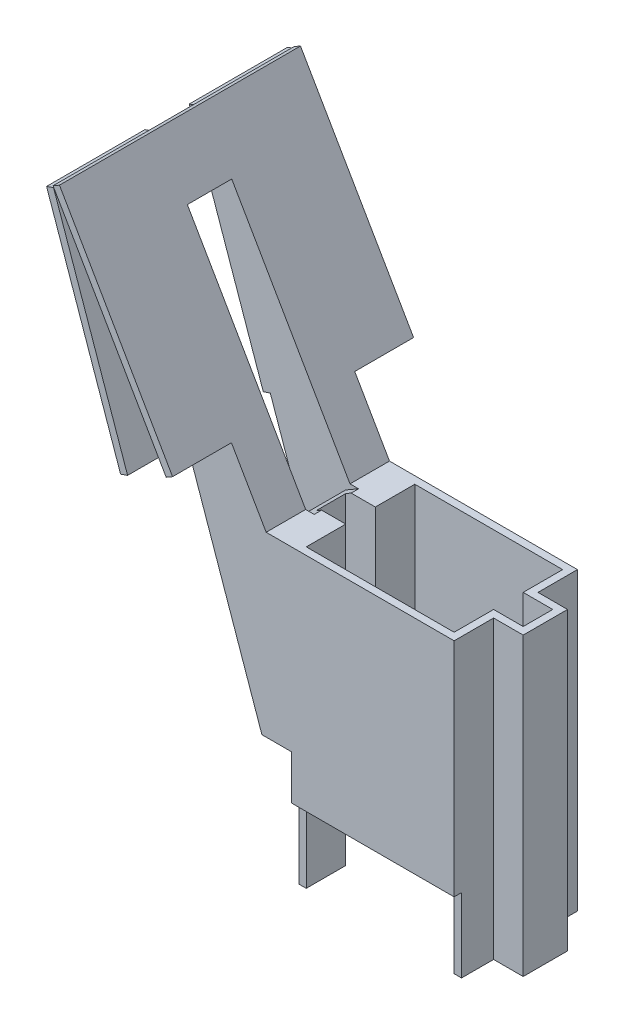
SolidWorks part; units mm, degrees
ref_plane "Ebene vorne" through (0, 0, 0) normal (0, 0, 1) x (1, 0, 0)
ref_plane "Ebene oben" through (0, 0, 0) normal (0, 1, 0) x (1, 0, 0)
ref_plane "Ebene rechts" through (0, 0, 0) normal (1, 0, 0) x (0, 0, -1)
sketch "Skizze1" plane through (0, 0, 0) normal (0, 1, 0) x (1, 0, 0)
  line L0 (-5, 1) -> (-5, 3.67)
  line L1 (5, -3.67) -> (-5, -3.67)
  line L2 (5, -3.67) -> (5, -1)
  line L3 (5, 3.67) -> (-5, 3.67)
  line L4 (-5, -3.67) -> (-5, -1)
  line L5 (5, -3.67) -> (-5, 3.67) construction
  line L6 (5, 3.67) -> (-5, -3.67) construction
  line L7 (7, -1) -> (5, -1)
  line L8 (7, -1) -> (7, 1)
  line L9 (7, 1) -> (5, 1)
  line L10 (-7, -1) -> (-7, 1)
  line L11 (7, -1) -> (-7, 1) construction
  line L12 (7, 1) -> (-7, -1) construction
  line L13 (5.5, -4.17) -> (-5.5, -4.17)
  line L14 (7.5, -1.5) -> (7.5, 1.5)
  line L15 (5.5, 4.17) -> (-5.5, 4.17)
  line L16 (-7.5, -1.5) -> (-7.5, 1.5)
  line L17 (5.5, -2.87) -> (-5.5, 2.87) construction
  line L18 (5.5, 3.21) -> (-5.5, -3.21) construction
  line L19 (-5, 1) -> (-7, 1)
  line L20 (5, 1) -> (5, 3.67)
  line L21 (-5, -1) -> (-7, -1)
  line L25 (-7.5, 1.5) -> (-5.5, 1.5)
  line L26 (-5.5, 4.17) -> (-5.5, 1.5)
  line L29 (7.5, 1.5) -> (5.5, 1.5)
  line L30 (5.5, 4.17) -> (5.5, 1.5)
  line L33 (7.5, -1.5) -> (5.5, -1.5)
  line L34 (5.5, -4.17) -> (5.5, -1.5)
  line L37 (-7.5, -1.5) -> (-5.5, -1.5)
  line L38 (-5.5, -4.17) -> (-5.5, -1.5)
  point P0 (0, 0)
  point P5 (0, 0)
  point P11 (0, 0)
  dimension "D1" = 10
  dimension "D2" = 2
  dimension "D3" = 14
  dimension "D4" = 0.5
  dimension "D5" = 0.5
  dimension "D6" = 7.34
  dimension "D7" = 0.5
  dimension "D8" = 0.5
  dimension "D9" = 0.5
  dimension "D10" = 0.5
  dimension "D11" = 0.5
  dimension "D12" = 0.5
extrude "Aufsatz-Linear austragen1" add sketch "Skizze1" along normal blind 20
sketch "Skizze8" plane through (0, 0, 3.67) normal (0, 0, -1) x (-1, 0, 0)
  line L0 (5.5, 20) -> (5.5, 0) construction
  line L1 (-5.5, 0) -> (5.5, 0)
  line L2 (-5.5, 0) -> (-5.5, 5)
  line L3 (-5.5, 5) -> (5.5, 5)
  line L4 (5.5, 0) -> (5.5, 5)
  dimension "D1" = 5
extrude "Schnitt-Linear austragen2" cut sketch "Skizze8" against normal up to next
sketch "Skizze10" plane through (0, 0, -4.17) normal (0, 0, -1) x (-1, 0, 0)
  line L1 (5.5, 20) -> (7.2113, 20)
  line L2 (5.5, 20) -> (5.5, 19.5)
  line L3 (5.5, 19.5) -> (7.5, 19.5)
  line L5 (7.5, 19.5) -> (17.6443, 37.0705)
  line L6 (17.6443, 37.0705) -> (17.2113, 37.3205)
  line L7 (17.2113, 37.3205) -> (7.2113, 20)
  line L8 (7.5, 20) -> (7.5, 0) construction
  dimension "D1" = 0.5
  dimension "D2" = 0.5
  dimension "D3" = 150
  dimension "D4" = 20
extrude "Aufsatz-Linear austragen3" add sketch "Skizze10" against normal up to vertex (8.34 mm away) up to point (-5.5, 20, 4.17)
sketch "Skizze12" plane through (0, 19.5, 0) normal (0, -1, 0) x (1, 0, 0)
  line L1 (-7, -1) -> (-5.5, -1)
  line L2 (-7, -1) -> (-7, 1)
  line L3 (-7, 1) -> (-5.5, 1)
  line L4 (-5.5, -1) -> (-5.5, 1)
extrude "Schnitt-Linear austragen3" cut sketch "Skizze12" against normal up to next
sketch "Skizze13" plane through (0, 0, -4.17) normal (0, 0, -1) x (-1, 0, 0)
  line L0 (17.2113, 37.3205) -> (9.5613, 24.0703)
  line L1 (17.2113, 37.3205) -> (7.2113, 20) construction
  line L2 (9.5613, 24.0703) -> (9.9943, 23.8203)
  line L3 (7.5, 19.5) -> (17.6443, 37.0705) construction
  line L4 (9.9943, 23.8203) -> (17.6443, 37.0705)
  line L5 (17.6443, 37.0705) -> (17.2113, 37.3205)
  dimension "D1" = 15.3
extrude "Aufsatz-Linear austragen4" add sketch "Skizze13" along normal blind 3.98
sketch "Skizze15" plane through (0, 0, -1.5) normal (0, 0, -1) x (-1, 0, 0)
  line L4 (5.5, 8) -> (5.5, 19.5)
  line L5 (5.5, 19.5) -> (7.5, 19.5)
  line L6 (7.5, 19.5) -> (17.6443, 37.0705)
  line L14 (17.6443, 37.0705) -> (7.5, 8)
  line L15 (7.5, 19.5) -> (7.5, 0) construction
  line L16 (7.5, 8) -> (5.5, 8)
  line L17 (5.5, 0) -> (7.5, 0) construction
  dimension "D1" = 8
extrude "Aufsatz-Linear austragen5" add sketch "Skizze15" along normal up to vertex
mirror "Spiegeln1" about plane through (0, 0, 0) normal (0, 0, 1) of "Aufsatz-Linear austragen4"
sketch "Skizze16" plane through (0, 0, 1.5) normal (0, 0, 1) x (1, 0, 0)
  line L0 (-17.6443, 37.0705) -> (-7.5, 8)
  line L1 (-7.5, 8) -> (-5.5, 8)
  line L2 (-5.5, 19.5) -> (-5.5, 5) construction
  line L3 (-5.5, 8) -> (-5.5, 19.5)
  line L4 (-5.5, 19.5) -> (-7.5, 19.5)
  line L5 (-7.5, 19.5) -> (-17.6443, 37.0705)
extrude "Aufsatz-Linear austragen6" add sketch "Skizze16" along normal up to vertex
sketch "Skizze17" plane through (2.8187, 1.6274, 0) normal (-0.866, -0.5, 0) x (0, 0, 1)
  line L0 (1.5, 40.9262) -> (1.5, 10.6782) construction
  line L1 (-1.5, 20.6375) -> (1.5, 20.6375)
  line L2 (-1.5, 20.6375) -> (-1.5, 36.9262)
  line L3 (-1.5, 36.9262) -> (1.5, 36.9262)
  line L4 (1.5, 20.6375) -> (1.5, 36.9262)
  line L6 (1.5, 40.9262) -> (-1.5, 40.9262) construction
  dimension "D1" = 4
extrude "Schnitt-Linear austragen4" cut sketch "Skizze17" against normal up to next
sketch "Skizze22" plane through (0, 0, -1.5) normal (0, 0, 1) x (1, 0, 0)
  line L0 (-17.6114, 36.9761) -> (-12.6034, 22.6248)
  line L1 (-17.6443, 37.0705) -> (-7.5, 8) construction
  line L2 (-12.6034, 22.6248) -> (-13.0755, 22.46)
  line L3 (-13.0755, 22.46) -> (-18.0835, 36.8114)
  line L4 (-18.0835, 36.8114) -> (-17.6114, 36.9761)
  point P4 (0, 0)
  point P8 (-17.5361, 36.7602)
  dimension "D1" = 15.2
  dimension "D2" = 0.5
  dimension "D3" = 0.1
extrude "Aufsatz-Linear austragen15" add sketch "Skizze22" against normal blind 6.65
mirror "Spiegeln2" about plane through (0, 0, 0) normal (0, 0, 1) of "Aufsatz-Linear austragen15"
